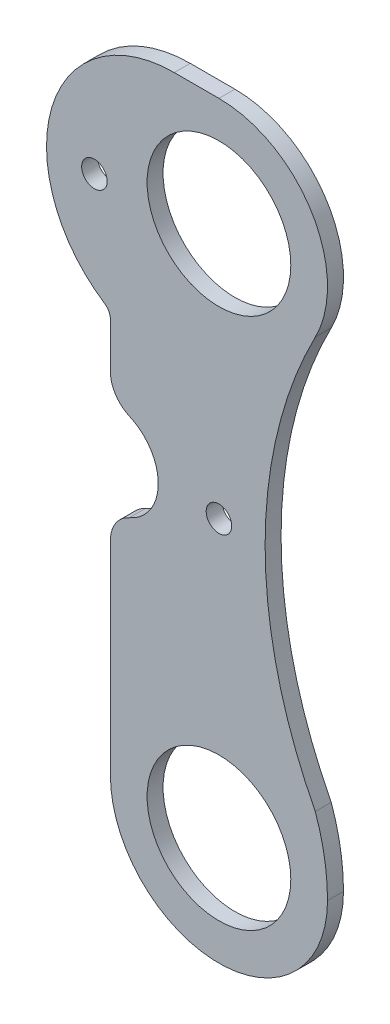
SolidWorks part; units mm, degrees
material "6061 Alloy"
ref_plane "Front Plane" through (0, 0, 0) normal (0, 0, 1) x (1, 0, 0)
ref_plane "Top Plane" through (0, 0, 0) normal (0, 1, 0) x (1, 0, 0)
ref_plane "Right Plane" through (0, 0, 0) normal (1, 0, 0) x (0, 0, -1)
sketch "Sketch1" plane through (0, 0, 0) normal (0, 0, 1) x (1, 0, 0)
  line L0 (0, 0) -> (0, -101.6) construction
  line L1 (21.59, -120.5575) -> (-21.59, -120.5575) construction
  line L2 (-8.89, 25.4) -> (8.89, 25.4)
  line L3 (-21.59, 12.7) -> (-21.59, -117.7751)
  line L5 (21.59, 12.7) -> (21.59, -117.7751)
  line L9 (-23.3829, -122.6853) -> (-33.2033, -134.3394)
  line L10 (-36.322, 25.4) -> (20.828, 25.4) construction
  line L11 (-36.322, 25.4) -> (-36.322, -203.2) construction
  line L12 (-36.322, -203.2) -> (20.828, -203.2) construction
  line L13 (20.828, 25.4) -> (20.828, -203.2) construction
  line L15 (-7.9527, -155.6168) -> (19.7971, -122.6853)
  line L16 (-32.4392, -143.2871) -> (-16.9004, -156.3809)
  circle A0 centre (0, 0) radius 38.1 construction
  circle A1 centre (0, -101.6) radius 38.1 construction
  circle A2 centre (0, 0) radius 14.2875
  circle A3 centre (0, -101.6) radius 14.2875
  arc A6 (8.89, 25.4) -> (21.59, 12.7) centre (8.89, 12.7) cw
  arc A7 (-8.89, 25.4) -> (-21.59, 12.7) centre (-8.89, 12.7) ccw
  circle A10 centre (-18.5321, -142.5501) radius 2.54
  arc A13 (-23.3829, -122.6853) -> (-21.59, -117.7751) centre (-29.21, -117.7751) ccw
  arc A14 (19.7971, -122.6853) -> (21.59, -117.7751) centre (13.97, -117.7751) ccw
  arc A15 (-16.9004, -156.3809) -> (-7.9527, -155.6168) centre (-12.8086, -151.525) ccw
  arc A16 (-33.2033, -134.3394) -> (-32.4392, -143.2871) centre (-28.3474, -138.4312) ccw
  circle A17 centre (0, -50.8) radius 2.54
  point P13 (-192.705, 39.2708)
  point P20 (21.59, 25.4)
  point P23 (-21.59, 25.4)
  point P31 (-36.322, -138.0404)
  dimension "D2" = 76.2
  dimension "D3" = 76.2
  dimension "D4" = 28.575
  dimension "D5" = 28.575
  dimension "D10" = 228.6
  dimension "D11" = 36.322
  dimension "D13" = 5.08
  dimension "D19" = 6.35
  dimension "D20" = 7.62
  dimension "D21" = 12.7
  dimension "D22" = 5.08
  dimension "D1" = 101.6
  dimension "D6" = 43.18
  dimension "D7" = 21.59
  dimension "D8" = 25.4
  dimension "D9" = 57.15
  dimension "D12" = 25.4
  dimension "D14" = 33.02
  dimension "D15" = 16.51
  dimension "D16" = 21.59
  dimension "D17" = 9.525
  dimension "D18" = 18.9575
extrude "Boss-Extrude1" add sketch "Sketch1" along normal blind 3.175
sketch "Sketch2" plane through (0, 0, 0) normal (0, 0, 1) x (1, 0, 0)
  line L0 (-21.59, -41.275) -> (-21.59, -60.325)
  line L1 (0, 0) -> (0, -101.6) construction
  line L4 (21.59, -117.7751) -> (21.59, 12.7) construction
  line L5 (-21.59, -50.8) -> (97.79, -50.8) construction
  line L6 (-21.59, 12.7) -> (-21.59, -117.7751) construction
  line L7 (0, 0) -> (-39.9512, 0) construction
  line L9 (16.51, -115.5122) -> (-17.5013, -155.8745)
  line L10 (-32.4392, -143.2871) -> (-16.9004, -156.3809) construction
  line L11 (-7.9527, -155.6168) -> (19.7971, -122.6853) construction
  line L13 (27.94, -121.6567) -> (-7.7896, -164.0581)
  line L14 (-7.7896, -164.0581) -> (-17.5013, -155.8745)
  line L15 (27.94, -121.6567) -> (27.94, 0)
  line L16 (27.94, 0) -> (21.59, 0)
  arc A1 (19.1591, -91.6472) -> (19.1591, -9.9528) centre (97.79, -50.8) cw
  arc A2 (-21.59, -60.325) -> (-21.59, -41.275) centre (-21.59, -50.8) ccw
  arc A3 (21.59, 0) -> (19.1591, -9.9528) centre (0, 0) cw
  arc A4 (21.59, -101.6) -> (19.1591, -91.6472) centre (0, -101.6) ccw
  arc A5 (21.59, -101.6) -> (16.51, -115.5122) centre (0, -101.6) cw
  point P24 (-2.7891, -158.1239)
  dimension "D2" = 12.7
  dimension "D3" = 50.8
  dimension "D4" = 6.35
  dimension "D1" = 76.2
  dimension "D5" = 19.05
extrude "Cut-Extrude1" cut sketch "Sketch2" along normal through all contours A1 A3 L16 L15 L13 L14 L9 A5 A4 | L0 A2
sketch "Sketch3" plane through (0, 0, 3.175) normal (0, 0, 1) x (1, 0, 0)
  line L0 (-27.3514, -127.3948) -> (-36.0255, -137.6886)
  line L3 (-27.3514, -127.3948) -> (-7.5576, -144.074)
  line L4 (-23.3829, -122.6853) -> (-33.2033, -134.3394) construction
  line L5 (16.51, -115.5122) -> (-17.5013, -155.8745) construction
  line L7 (-35.4064, -144.9387) -> (-24.4031, -154.2106)
  line L8 (-23.3829, -122.6853) -> (-33.2033, -134.3394) construction
  line L9 (-7.5576, -144.074) -> (-15.4554, -153.4465)
  line L10 (-32.4392, -143.2871) -> (-17.5013, -155.8745) construction
  circle A2 centre (-18.5321, -142.5501) radius 2.54
  circle A3 centre (-18.5321, -142.5501) radius 2.54 construction
  arc A5 (-36.0255, -137.6886) -> (-35.4064, -144.9387) centre (-32.0909, -141.0041) ccw
  arc A6 (-24.4031, -154.2106) -> (-15.4554, -153.4465) centre (-20.3113, -149.3547) ccw
  dimension "D2" = 6.35
  dimension "D3" = 5.1453
  dimension "D1" = 3.175
fillet "Fillet3" radius 6.35 2 edges at (-21.59, -60.325, 1.5875) (-21.59, -41.275, 1.5875)
extrude "Boss-Extrude3" add sketch "Sketch3" against normal blind 3.175
sketch "Sketch6" plane through (0, 0, 3.175) normal (0, 0, 1) x (1, 0, 0)
  line L0 (-35.4064, -144.9387) -> (-63.6204, -121.1641)
  line L1 (-63.6204, -121.1641) -> (-51.345, -106.5965)
  line L2 (-51.345, -106.5965) -> (-27.0656, -127.0555)
  line L4 (-35.4064, -144.9387) -> (-24.4031, -154.2106) construction
  line L5 (-23.3829, -122.6853) -> (-36.0255, -137.6886) construction
  line L6 (-35.4064, -144.9387) -> (-27.0656, -127.0555)
  circle A0 centre (-52.6268, -117.9721) radius 2.54
  dimension "D4" = 5.08
  dimension "D1" = 31.75
  dimension "D2" = 9.525
  dimension "1" = 19.05
  dimension "D3" = 6.35
extrude "Boss-Extrude4" add sketch "Sketch6" against normal blind 3.175
fillet "Fillet2" radius 6.35 3 edges at (-63.6204, -121.1641, 1.5875) (-51.345, -106.5965, 1.5875) (-27.0656, -127.0555, 1.5875)
sketch "Sketch7" plane through (0, 0, 3.175) normal (0, 0, 1) x (1, 0, 0)
  line L0 (-21.59, 12.7) -> (-21.59, -36.2503) construction
  line L1 (21.59, 0) -> (21.59, 12.7) construction
  line L2 (-21.59, 0) -> (21.59, 0) construction
  line L3 (-21.59, 0) -> (-21.59, 31.75)
  line L4 (-21.59, 31.75) -> (21.59, 31.75)
  line L5 (21.59, 31.75) -> (21.59, 0)
  line L6 (8.89, 25.4) -> (-8.89, 25.4) construction
  arc A0 (-21.59, 0) -> (21.59, 0) centre (0, 0) cw
  dimension "D1" = 6.35
extrude "Cut-Extrude2" cut sketch "Sketch7" against normal through all
sketch "Sketch10" plane through (0, 0, 3.175) normal (0, 0, 1) x (1, 0, 0)
  line L0 (16.51, -115.5122) -> (-17.5013, -155.8745) construction
  line L1 (-18.1519, -155.3263) -> (-17.3615, -157.512)
  line L2 (-17.3615, -157.512) -> (-14.3757, -156.4323)
  line L3 (-14.3757, -156.4323) -> (-15.4554, -153.4465)
  line L5 (-18.1519, -155.3263) -> (-17.5013, -155.8745) construction
  circle A0 centre (-20.3113, -149.3547) radius 6.35 construction
  arc A1 (-24.4031, -154.2106) -> (-18.1519, -155.3263) centre (-20.3113, -149.3547) ccw construction
  arc A2 (-18.1519, -155.3263) -> (-15.4554, -153.4465) centre (-20.3113, -149.3547) ccw
  dimension "D1" = 3.175
  dimension "D2" = 30
extrude "Cut-Extrude3" cut sketch "Sketch10" against normal through all
sketch "Sketch12" plane through (0, 0, 3.175) normal (0, 0, 1) x (1, 0, 0)
  line L0 (-21.59, -65.3497) -> (-21.59, -117.7751) construction
  line L1 (-21.59, -101.6) -> (-72.39, -101.6)
  line L2 (-72.39, -101.6) -> (-72.39, -165.1)
  line L3 (-72.39, -165.1) -> (16.51, -165.1)
  line L4 (16.51, -165.1) -> (16.51, -115.5122)
  arc A2 (16.51, -115.5122) -> (-21.59, -101.6) centre (0, -101.6) cw
  dimension "D1" = 63.5
  dimension "D2" = 88.9
extrude "Cut-Extrude4" cut sketch "Sketch12" against normal through all
sketch "Sketch15" plane through (0, 0, 3.175) normal (0, 0, 1) x (1, 0, 0)
  line L0 (-21.59, 0) -> (-21.59, -36.2503) construction
  line L5 (-21.59, -29.21) -> (-21.59, 0)
  line L7 (0, 21.59) -> (-16.6076, 6.9565)
  line L8 (-16.6076, 6.9565) -> (-12.5785, -28.9408)
  line L9 (-8.89, 21.59) -> (0, 21.59)
  arc A0 (-12.5785, -28.9408) -> (-34.29, -3.81) centre (-8.89, -3.81) cw
  arc A1 (-8.89, 21.59) -> (-34.29, -3.81) centre (-8.89, -3.81) ccw
  circle A2 centre (-24.765, -3.81) radius 2.54
  arc A3 (19.1591, -9.9528) -> (-21.59, 0) centre (0, 0) ccw construction
  point P10 (0, 0)
  arc M10 (19.1591, -9.9528) -> (-21.59, 0) centre (0, 0) ccw
  line M11 (-21.59, 0) -> (-21.59, -36.2503)
  dimension "D1" = 12.7
  dimension "D4" = 3.175
  dimension "D3" = 5.08
  dimension "D2" = 25.4
extrude "Boss-Extrude8" add sketch "Sketch15" against normal blind 3.175 contours L9 A1 A0 A2 M11 M10
fillet "Fillet4" radius 2.54 1 edges at (-21.59, -25.807, 1.5875)
sketch "Sketch16" plane through (0, 0, 3.175) normal (0, 0, 1) x (1, 0, 0)
  line L0 (-21.59, -101.6) -> (-21.59, -105.7758)
  line L1 (0, -102.5377) -> (0, -93.0735) construction
  line L2 (0, -101.6) -> (-11.1927, -101.6) construction
  line L3 (21.59, -105.7758) -> (21.59, -101.6)
  line L4 (-21.59, -101.6) -> (-1.4895, -121.7005)
  line L5 (-1.4895, -121.7005) -> (4.5179, -121.7005)
  line L6 (4.5179, -121.7005) -> (21.59, -101.6)
  arc A0 (-21.59, -105.7758) -> (21.59, -105.7758) centre (0, -105.7758) ccw
  arc A1 (-21.59, -101.6) -> (19.1591, -91.6472) centre (0, -101.6) ccw construction
  dimension "D1" = 4.1758
  dimension "D2" = 4.1758
extrude "Boss-Extrude9" add sketch "Sketch16" against normal through all contours L6 L3 A0 L0 L4 L5
sketch "Sketch17" plane through (0, 0, 3.175) normal (0, 0, 1) x (1, 0, 0)
  circle A0 centre (0, -101.6) radius 14.2875
  circle A1 centre (0, -101.6) radius 14.2875 construction
extrude "Boss-Extrude10" add sketch "Sketch17" against normal through all
sketch "Sketch19" plane through (0, 0, 3.175) normal (0, 0, 1) x (1, 0, 0)
  line L0 (21.59, -105.7758) -> (21.59, -97.4446) construction
  line L1 (19.1591, -91.6472) -> (21.59, -91.6472)
  line L2 (21.59, -91.6472) -> (21.59, -105.7758)
  arc A0 (19.1591, -91.6472) -> (21.59, -105.7758) centre (-20.6831, -105.7758) cw
extrude "Cut-Extrude5" cut sketch "Sketch19" against normal through all
sketch "Sketch20" plane through (0, 0, 3.175) normal (0, 0, 1) x (1, 0, 0)
  circle A0 centre (0, -105.7758) radius 14.2875
  arc A1 (-21.59, -105.7758) -> (21.59, -105.7758) centre (0, -105.7758) ccw construction
  point P2 (0, -105.8516)
  dimension "D1" = 28.575
extrude "Cut-Extrude6" cut sketch "Sketch20" against normal through all
